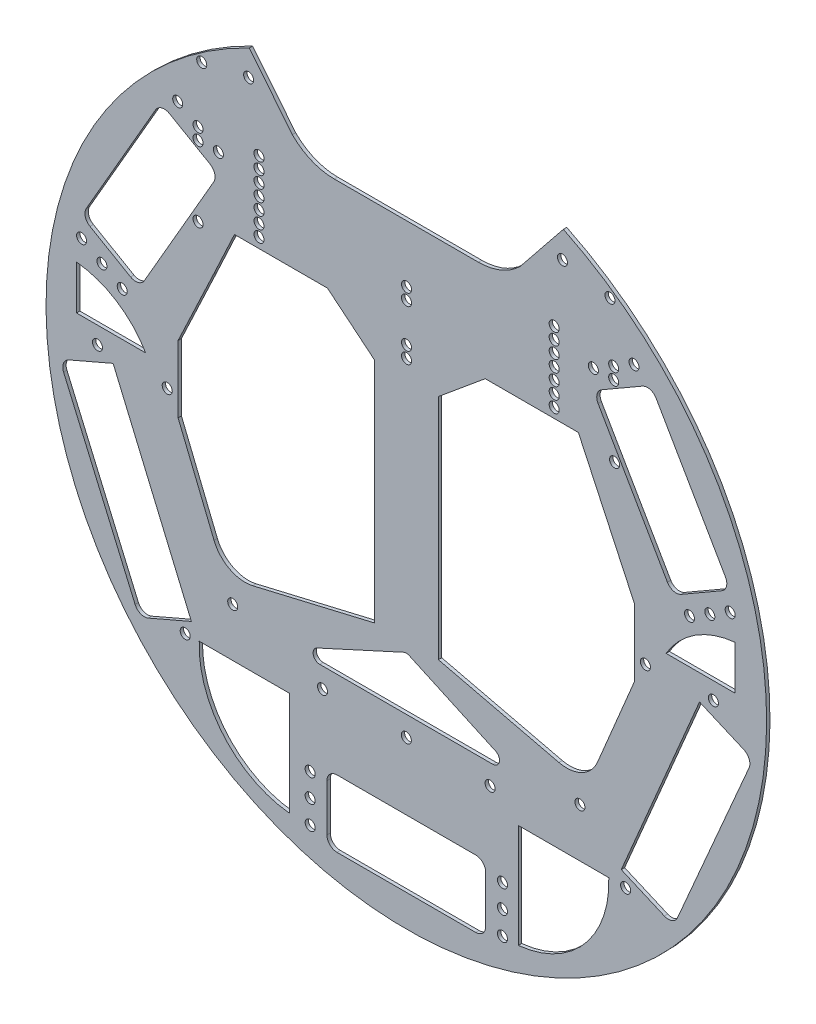
SolidWorks part; units mm, degrees
ref_plane "Alzado" through (0, 0, 0) normal (0, 0, 1) x (1, 0, 0)
ref_plane "Planta" through (0, 0, 0) normal (0, 1, 0) x (1, 0, 0)
ref_plane "Vista lateral" through (0, 0, 0) normal (1, 0, 0) x (0, 0, -1)
sketch "Model" plane through (0, 0, 0) normal (0, 0, 1) x (1, 0, 0)
  line L0 (-144.9822, 112.1716) -> (-132.1241, 96.1716)
  line L1 (-196.5067, 17.9216) -> (-175.8858, 17.9216)
  line L2 (-0.0098, 31.0807) -> (-0.0098, 17.9216)
  line L3 (-159.9087, -48.5784) -> (-132.9087, -48.5784)
  line L4 (-64.7202, -48.5784) -> (-64.7202, -79.5784)
  line L5 (-179.0521, -48.6344) -> (-200.3744, 0.7041)
  line L6 (-155.4955, -20.3043) -> (-166.214, 5.9757)
  line L7 (-52.6096, -26.2509) -> (-88.5567, -17.6869)
  line L8 (-156.6996, 76.318) -> (-168.8239, 83.318)
  line L9 (-16.1341, 35.4109) -> (-4.0098, 42.4109)
  line L10 (-121.808, -65.5784) -> (-121.808, -79.5784)
  line L11 (-51.2659, 112.1716) -> (-64.1241, 96.1716)
  line L12 (-76.6241, 90.994) -> (-119.6241, 90.994)
  line L13 (-196.5067, 31.0807) -> (-196.5067, 17.9216)
  line L14 (-0.0098, 17.9216) -> (-20.6306, 17.9216)
  line L15 (-132.9087, -48.5784) -> (-132.9087, -79.5784)
  line L16 (-64.7202, -48.5784) -> (-37.7202, -48.5784)
  line L17 (4.1263, 0.7041) -> (-17.1961, -48.6344)
  line L18 (-185.5985, 10.3579) -> (-198.8107, 4.648)
  line L19 (-162.2523, -44.6423) -> (-175.1081, -50.1981)
  line L20 (-166.214, 25.9757) -> (-166.214, 5.9757)
  line L21 (-155.6486, 48.3648) -> (-166.214, 25.9757)
  line L22 (-155.6486, 48.3648) -> (-149.3966, 61.7721)
  line L23 (-121.6454, 61.7721) -> (-107.6666, 50.2717)
  line L24 (-107.6666, 50.2717) -> (-107.6666, -17.7283)
  line L25 (-143.9464, -26.262) -> (-107.6666, -17.7283)
  line L26 (-88.5567, -17.6869) -> (-88.5567, 50.3131)
  line L27 (-88.5567, 50.3131) -> (-74.5862, 61.9085)
  line L28 (-46.7898, 61.9085) -> (-30.0341, 25.9757)
  line L29 (-30.0341, 25.9757) -> (-30.0341, 5.9757)
  line L30 (-41.0676, -20.3842) -> (-30.0341, 5.9757)
  line L31 (-155.6015, 72.2199) -> (-176.2842, 36.3964)
  line L32 (-180.3823, 35.2983) -> (-192.5067, 42.2983)
  line L33 (-172.922, 82.2199) -> (-193.6047, 46.3964)
  line L34 (-20.2322, 36.509) -> (-40.916, 72.3343)
  line L35 (-39.8179, 76.4324) -> (-27.6936, 83.4324)
  line L36 (-2.9117, 46.509) -> (-23.5955, 82.3343)
  line L37 (-77.4404, -62.5784) -> (-118.808, -62.5784)
  line L38 (-74.4404, -65.5784) -> (-74.4404, -79.5784)
  line L39 (-77.4404, -82.5784) -> (-118.808, -82.5784)
  line L40 (-123.9387, -36.5784) -> (-72.3097, -36.5784)
  line L41 (-124.7702, -32.7594) -> (-98.9557, -20.9585)
  line L42 (-71.4781, -32.7594) -> (-97.2927, -20.9585)
  line L100 (-162.2523, -44.6423) -> (-185.5985, 10.3579)
  line L101 (-10.6497, 10.3579) -> (-33.9958, -44.6423)
  line L102 (-33.9958, -44.6423) -> (-21.14, -50.1981)
  line L103 (2.5625, 4.648) -> (-10.6497, 10.3579)
  line L104 (-121.6454, 61.7721) -> (-149.3966, 61.7721)
  line L105 (-74.5862, 61.9085) -> (-46.7898, 61.9085)
  line L142 (-43.3072, 37.4625) -> (-43.3072, -14.6812)
  line L143 (-43.3072, 37.4625) -> (-43.3072, 45.0688)
  line L144 (-63.8628, 20.2125) -> (-64.3072, 20.2125)
  line L145 (-64.3072, 20.2125) -> (-61.3072, 20.2125)
  line L146 (-61.3072, 20.2125) -> (-61.3072, 14.9625)
  line L147 (-61.3072, 14.9625) -> (-61.3072, 9.7125)
  line L148 (-61.3072, 9.7125) -> (-64.3072, 9.7125)
  line L149 (-43.3072, 20.4625) -> (-46.8072, 20.4625)
  line L150 (-48.3072, 18.9625) -> (-48.3072, 10.9625)
  line L151 (-46.8072, 9.4625) -> (-43.3072, 9.4625)
  line L152 (-64.3072, 45.0688) -> (-64.3072, 20.2125)
  line L153 (-64.3072, 9.7125) -> (-64.3072, -14.6812)
  line L154 (-43.3072, -14.6812) -> (-64.3072, -14.6812)
  line L155 (-85.3072, 37.4625) -> (-85.3072, -14.6812)
  line L156 (-64.7516, 20.2125) -> (-64.3072, 20.2125)
  line L157 (-64.3072, 20.2125) -> (-67.3072, 20.2125)
  line L158 (-67.3072, 20.2125) -> (-67.3072, 14.9625)
  line L159 (-67.3072, 14.9625) -> (-67.3072, 9.7125)
  line L160 (-67.3072, 9.7125) -> (-64.3072, 9.7125)
  line L161 (-85.3072, 20.4625) -> (-81.8072, 20.4625)
  line L162 (-80.3072, 18.9625) -> (-80.3072, 10.9625)
  line L163 (-81.8072, 9.4625) -> (-85.3072, 9.4625)
  line L164 (-64.3072, -14.6812) -> (-85.3072, -14.6812)
  line L165 (-85.3072, 37.4625) -> (-85.3072, 45.0688)
  line L166 (-43.3072, 45.0688) -> (-85.3072, 45.0688)
  line L167 (-112.0146, 38.2592) -> (-112.0146, -13.8844)
  line L168 (-112.0146, 38.2592) -> (-112.0146, 45.8656)
  line L169 (-132.5703, 21.0092) -> (-133.0146, 21.0092)
  line L170 (-133.0146, 21.0092) -> (-130.0146, 21.0092)
  line L171 (-130.0146, 21.0092) -> (-130.0146, 15.7592)
  line L172 (-130.0146, 15.7592) -> (-130.0146, 10.5092)
  line L173 (-130.0146, 10.5092) -> (-133.0146, 10.5092)
  line L174 (-112.0146, 21.2592) -> (-115.5146, 21.2592)
  line L175 (-117.0146, 19.7592) -> (-117.0146, 11.7592)
  line L176 (-115.5146, 10.2592) -> (-112.0146, 10.2592)
  line L177 (-133.0146, 45.8656) -> (-133.0146, 21.0092)
  line L178 (-133.0146, 10.5092) -> (-133.0146, -13.8844)
  line L179 (-112.0146, -13.8844) -> (-133.0146, -13.8844)
  line L180 (-154.0146, 38.2592) -> (-154.0146, -13.8844)
  line L181 (-133.459, 21.0092) -> (-133.0146, 21.0092)
  line L182 (-133.0146, 21.0092) -> (-136.0146, 21.0092)
  line L183 (-136.0146, 21.0092) -> (-136.0146, 15.7592)
  line L184 (-136.0146, 15.7592) -> (-136.0146, 10.5092)
  line L185 (-136.0146, 10.5092) -> (-133.0146, 10.5092)
  line L186 (-154.0146, 21.2592) -> (-150.5146, 21.2592)
  line L187 (-149.0146, 19.7592) -> (-149.0146, 11.7592)
  line L188 (-150.5146, 10.2592) -> (-154.0146, 10.2592)
  line L189 (-133.0146, -13.8844) -> (-154.0146, -13.8844)
  line L190 (-154.0146, 38.2592) -> (-154.0146, 45.8656)
  line L191 (-112.0146, 45.8656) -> (-154.0146, 45.8656)
  circle A0 centre (-36.2557, 84.2625) radius 1.5
  circle A1 centre (-7.5719, 34.5807) radius 1.5
  circle A2 centre (-126.808, -72.5784) radius 1.5
  circle A3 centre (-69.4404, -72.5784) radius 1.5
  circle A4 centre (-188.9445, 34.4682) radius 1.5
  circle A5 centre (-160.2617, 84.1481) radius 1.5
  circle A6 centre (-98.1242, -42.5784) radius 1.5
  circle A7 centre (-149.9196, -34.0276) radius 1.5
  circle A8 centre (-169.4562, 11.9976) radius 1.5
  circle A9 centre (-46.3285, -34.0276) radius 1.5
  circle A10 centre (-26.792, 11.9976) radius 1.5
  circle A11 centre (-164.0915, -48.6928) radius 1.5
  circle A12 centre (-32.6953, -48.6928) radius 1.5
  circle A13 centre (-190.276, 12.8072) radius 1.5
  circle A14 centre (-6.5108, 12.8072) radius 1.5
  circle A15 centre (-195.0067, 37.9682) radius 1.5
  circle A16 centre (-182.8823, 30.9682) radius 1.5
  circle A17 centre (-166.3239, 87.6481) radius 1.5
  circle A18 centre (-154.1996, 80.6481) radius 1.5
  circle A19 centre (-13.6341, 31.0807) radius 1.5
  circle A20 centre (-1.5098, 38.0807) radius 1.5
  circle A21 centre (-42.3179, 80.7625) radius 1.5
  circle A22 centre (-30.1936, 87.7625) radius 1.5
  circle A23 centre (-126.808, -65.6928) radius 1.5
  circle A24 centre (-69.4404, -65.6928) radius 1.5
  circle A25 centre (-69.4404, -79.5784) radius 1.5
  circle A26 centre (-126.808, -79.5784) radius 1.5
  circle A27 centre (-145.1615, 104.4471) radius 1.5
  circle A28 centre (-51.5418, 104.1338) radius 1.5
  circle A29 centre (-98.0672, 70.4275) radius 1.5
  circle A30 centre (-98.0672, 55.4275) radius 1.5
  circle A31 centre (-123.1242, -42.5784) radius 1.5
  circle A32 centre (-73.1242, -42.5784) radius 1.5
  arc A33 (-72.3097, -36.5784) -> (-71.4781, -32.7594) centre (-72.3097, -34.5784) ccw
  arc A34 (-144.9822, 112.1716) -> (-51.2659, 112.1716) centre (-98.1241, 15.4216) ccw
  arc A35 (-76.6241, 90.994) -> (-64.1241, 96.1716) centre (-76.6241, 108.6716) ccw
  arc A36 (-132.1241, 96.1716) -> (-119.6241, 90.994) centre (-119.6241, 108.6716) ccw
  arc A37 (-175.8858, 17.9216) -> (-196.5067, 31.0807) centre (-199.0952, 4.2881) ccw
  arc A38 (-0.0098, 31.0807) -> (-20.6306, 17.9216) centre (2.5788, 4.2881) ccw
  arc A39 (-159.9087, -48.5784) -> (-132.9087, -79.5784) centre (-129.9439, -49.738) ccw
  arc A40 (-64.7202, -79.5784) -> (-37.7202, -48.5784) centre (-67.685, -49.738) ccw
  arc A41 (4.1263, 0.7041) -> (2.5625, 4.648) centre (1.3724, 1.8942) ccw
  arc A42 (-21.14, -50.1981) -> (-17.1961, -48.6344) centre (-19.9499, -47.4443) ccw
  arc A43 (-198.8107, 4.648) -> (-200.3744, 0.7041) centre (-197.6206, 1.8942) ccw
  arc A44 (-179.0521, -48.6344) -> (-175.1081, -50.1981) centre (-176.2982, -47.4443) ccw
  arc A45 (-155.4955, -20.3043) -> (-143.9464, -26.262) centre (-146.2361, -16.5277) ccw
  arc A46 (-52.6096, -26.2509) -> (-41.0676, -20.3842) centre (-50.2921, -16.5231) ccw
  arc A47 (-155.6015, 72.2199) -> (-156.6996, 76.318) centre (-158.1996, 73.7199) ccw
  arc A48 (-180.3823, 35.2983) -> (-176.2842, 36.3964) centre (-178.8823, 37.8964) ccw
  arc A49 (-193.6047, 46.3964) -> (-192.5067, 42.2983) centre (-191.0067, 44.8964) ccw
  arc A50 (-168.8239, 83.318) -> (-172.922, 82.2199) centre (-170.3239, 80.7199) ccw
  arc A51 (-20.2322, 36.509) -> (-16.1341, 35.4109) centre (-17.6341, 38.009) ccw
  arc A52 (-39.8179, 76.4324) -> (-40.916, 72.3343) centre (-38.3179, 73.8343) ccw
  arc A53 (-23.5955, 82.3343) -> (-27.6936, 83.4324) centre (-26.1936, 80.8343) ccw
  arc A54 (-4.0098, 42.4109) -> (-2.9117, 46.509) centre (-5.5098, 45.009) ccw
  arc A55 (-118.808, -62.5784) -> (-121.808, -65.5784) centre (-118.808, -65.5784) ccw
  arc A56 (-74.4404, -65.5784) -> (-77.4404, -62.5784) centre (-77.4404, -65.5784) ccw
  arc A57 (-77.4404, -82.5784) -> (-74.4404, -79.5784) centre (-77.4404, -79.5784) ccw
  arc A58 (-121.808, -79.5784) -> (-118.808, -82.5784) centre (-118.808, -79.5784) ccw
  arc A59 (-124.7702, -32.7594) -> (-123.9387, -36.5784) centre (-123.9387, -34.5784) ccw
  arc A60 (-97.2927, -20.9585) -> (-98.9557, -20.9585) centre (-98.1242, -22.7774) ccw
  circle A137 centre (-98.0672, 58.8932) radius 1.5
  circle A138 centre (-98.0672, 73.8932) radius 1.5
  circle A139 centre (-159.1647, 101.3816) radius 1.5
  circle A140 centre (-37.3747, 101.3908) radius 1.5
  circle A141 centre (-142.0742, 64.7713) radius 1.5
  circle A142 centre (-54.012, 64.771) radius 1.5
  circle A174 centre (-53.8072, 27.4625) radius 8.5
  circle A175 centre (-53.8072, 2.4625) radius 8.5
  arc A176 (-46.8072, 20.4625) -> (-48.3072, 18.9625) centre (-46.8072, 18.9625) ccw
  arc A177 (-48.3072, 10.9625) -> (-46.8072, 9.4625) centre (-46.8072, 10.9625) ccw
  circle A178 centre (-45.0072, 35.7625) radius 1.5
  circle A179 centre (-45.0072, -5.8375) radius 1.5
  circle A180 centre (-62.6072, 35.7625) radius 1.5
  circle A181 centre (-62.6072, -5.8375) radius 1.5
  circle A182 centre (-59.3072, -10.5375) radius 1.75
  circle A183 centre (-49.3072, -10.5375) radius 1.75
  circle A184 centre (-59.3072, 40.4625) radius 1.75
  circle A185 centre (-49.3072, 40.4625) radius 1.75
  circle A186 centre (-74.8072, 27.4625) radius 8.5
  circle A187 centre (-74.8072, 2.4625) radius 8.5
  arc A188 (-80.3072, 18.9625) -> (-81.8072, 20.4625) centre (-81.8072, 18.9625) ccw
  arc A189 (-81.8072, 9.4625) -> (-80.3072, 10.9625) centre (-81.8072, 10.9625) ccw
  circle A190 centre (-83.6072, 35.7625) radius 1.5
  circle A191 centre (-66.0072, 35.7625) radius 1.5
  circle A192 centre (-66.0072, -5.8375) radius 1.5
  circle A193 centre (-69.3072, -10.5375) radius 1.75
  circle A194 centre (-69.3072, 40.4625) radius 1.75
  circle A195 centre (-79.3072, 40.4625) radius 1.75
  circle A196 centre (-79.3072, -10.5375) radius 1.5
  circle A197 centre (-122.5146, 28.2592) radius 8.5
  circle A198 centre (-122.5146, 3.2592) radius 8.5
  arc A199 (-115.5146, 21.2592) -> (-117.0146, 19.7592) centre (-115.5146, 19.7592) ccw
  arc A200 (-117.0146, 11.7592) -> (-115.5146, 10.2592) centre (-115.5146, 11.7592) ccw
  circle A201 centre (-113.7146, 36.5592) radius 1.5
  circle A202 centre (-113.7146, -5.0408) radius 1.5
  circle A203 centre (-131.3146, 36.5592) radius 1.5
  circle A204 centre (-131.3146, -5.0408) radius 1.5
  circle A205 centre (-128.0146, -9.7408) radius 1.75
  circle A206 centre (-118.0146, -9.7408) radius 1.75
  circle A207 centre (-128.0146, 41.2592) radius 1.75
  circle A208 centre (-118.0146, 41.2592) radius 1.75
  circle A209 centre (-143.5146, 28.2592) radius 8.5
  circle A210 centre (-143.5146, 3.2592) radius 8.5
  arc A211 (-149.0146, 19.7592) -> (-150.5146, 21.2592) centre (-150.5146, 19.7592) ccw
  arc A212 (-150.5146, 10.2592) -> (-149.0146, 11.7592) centre (-150.5146, 11.7592) ccw
  circle A213 centre (-152.3146, 36.5592) radius 1.5
  circle A214 centre (-134.7146, 36.5592) radius 1.5
  circle A215 centre (-134.7146, -5.0408) radius 1.5
  circle A216 centre (-138.0146, -9.7408) radius 1.75
  circle A217 centre (-138.0146, 41.2592) radius 1.75
  circle A218 centre (-148.0146, 41.2592) radius 1.75
  circle A219 centre (-148.0146, -9.7408) radius 1.5
  circle A313 centre (-36.2557, 80.7625) radius 1.5
  circle A314 centre (-160.2617, 80.6481) radius 1.5
  circle A315 centre (-160.2617, 59.6481) radius 1.5
  circle A316 centre (-35.9864, 59.6481) radius 1.5
  circle A317 centre (-54.012, 68.271) radius 1.5
  circle A318 centre (-54.012, 71.771) radius 1.5
  circle A319 centre (-54.012, 75.271) radius 1.5
  circle A320 centre (-54.012, 78.771) radius 1.5
  circle A321 centre (-54.012, 82.271) radius 1.5
  circle A322 centre (-54.012, 85.771) radius 1.5
  circle A323 centre (-142.0742, 68.2713) radius 1.5
  circle A324 centre (-142.0742, 71.7713) radius 1.5
  circle A325 centre (-142.0742, 75.2713) radius 1.5
  circle A326 centre (-142.0742, 78.7713) radius 1.5
  circle A327 centre (-142.0742, 82.2713) radius 1.5
  circle A328 centre (-142.0742, 85.7713) radius 1.5
extrude "Saliente-Extruir1" add sketch "Model" along normal blind 1 contours A36 L0 A34 L11 A35 L12 A328 A327 A326 A325 A324 A323 A322 A321 A320 A319 A318 A317 A316 A315 A314 A313 A142 A141 A140 A139 A138 A137
